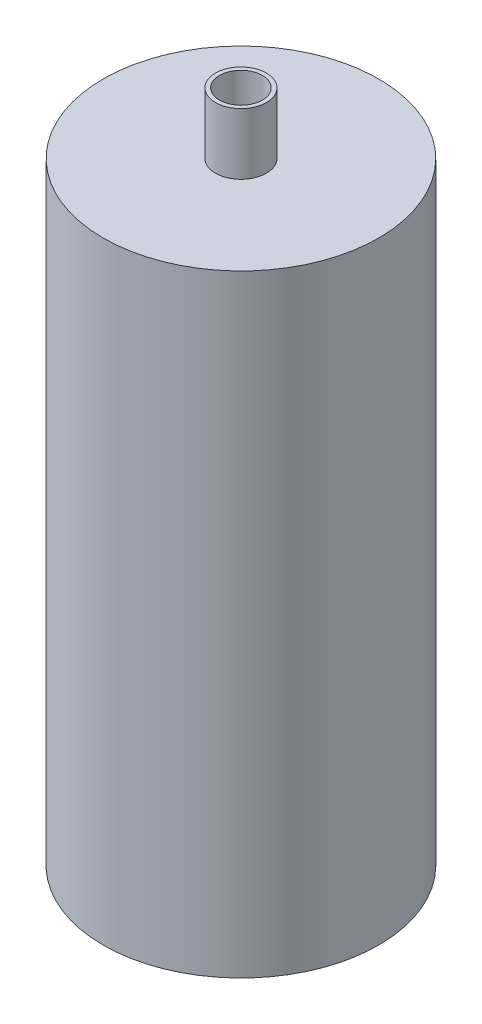
SolidWorks part; units mm, degrees
ref_plane "Front Plane" through (0, 0, 0) normal (0, 0, 1) x (1, 0, 0)
ref_plane "Top Plane" through (0, 0, 0) normal (0, 1, 0) x (1, 0, 0)
ref_plane "Right Plane" through (0, 0, 0) normal (1, 0, 0) x (0, 0, -1)
sketch "Sketch1" plane through (0, 0, 0) normal (0, 1, 0) x (1, 0, 0)
  circle A0 centre (0, 0) radius 13.5
  dimension "D1" = 27
extrude "Boss-Extrude1" add sketch "Sketch1" along normal blind 60
sketch "Sketch2" plane through (0, 60, 0) normal (0, 1, 0) x (1, 0, 0)
  circle A0 centre (0, 0) radius 2.5
  dimension "D1" = 5
extrude "Boss-Extrude2" add sketch "Sketch2" along normal blind 6
sketch "Sketch3" plane through (0, 66, 0) normal (0, 1, 0) x (1, 0, 0)
  circle A0 centre (0, 0) radius 2.1
  circle A1 centre (0, 0) radius 2.5 construction
  dimension "D1" = 0.4
extrude "Cut-Extrude1" cut sketch "Sketch3" against normal through all
